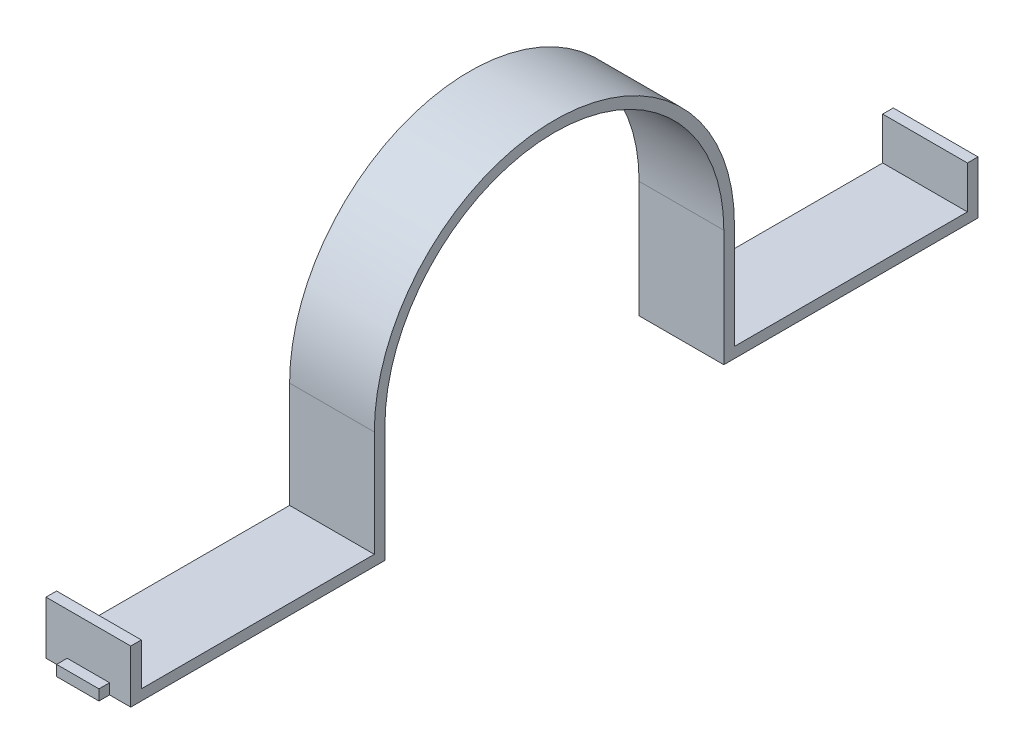
SolidWorks part; units mm, degrees
ref_plane "Front Plane" through (0, 0, 0) normal (0, 0, 1) x (1, 0, 0)
ref_plane "Top Plane" through (0, 0, 0) normal (0, 1, 0) x (1, 0, 0)
ref_plane "Right Plane" through (0, 0, 0) normal (1, 0, 0) x (0, 0, -1)
sketch "Sketch1" plane through (0, 0, 0) normal (1, 0, 0) x (0, 0, -1)
  line L2 (-107.95, 0) -> (-107.95, -69.85)
  line L3 (-107.95, -69.85) -> (-101.6, -69.85)
  line L4 (-101.6, -69.85) -> (-101.6, 0)
  line L6 (101.6, -69.85) -> (107.95, -69.85)
  line L7 (107.95, -69.85) -> (107.95, 0)
  line L8 (101.6, 0) -> (101.6, -69.85)
  arc A0 (-101.6, 0) -> (101.6, 0) centre (0, 0) cw
  arc A2 (-107.95, 0) -> (107.95, 0) centre (0, 0) cw
  point P9 (0, 101.6)
  dimension "D1" = 101.6
  dimension "D2" = 107.95
  dimension "D3" = 101.6
  dimension "D4" = 69.85
extrude "Boss-Extrude1" add sketch "Sketch1" along normal mid plane 50.8
ref_plane "Plane1" through (0, 0, 254) normal (0, 0, 1) x (1, 0, 0)
sketch "Sketch2" plane through (0, 0, 254) normal (0, 0, 1) x (1, 0, 0)
  line L0 (25.4, 0) -> (25.4, 107.95) construction
  line L1 (-25.4, -69.85) -> (25.4, -69.85)
  line L2 (-25.4, -69.85) -> (-25.4, -63.5)
  line L3 (-25.4, -63.5) -> (25.4, -63.5)
  line L4 (25.4, -69.85) -> (25.4, -63.5)
  dimension "D1" = 6.35
extrude "Boss-Extrude2" add sketch "Sketch2" against normal up to body separate body
mirror "Mirror1" about plane through (0, 0, 0) normal (0, 0, 1) of "Boss-Extrude2"
sketch "Sketch3" plane through (0, -63.5, 0) normal (0, 1, 0) x (1, 0, 0)
  line L0 (-27.94, -254) -> (27.94, -254) construction
  line L1 (-12.7, -254) -> (12.7, -254)
  line L2 (-12.7, -254) -> (-12.7, -260.35)
  line L3 (-12.7, -260.35) -> (12.7, -260.35)
  line L4 (12.7, -254) -> (12.7, -260.35)
  line L5 (-25.4, -107.95) -> (-25.4, -254) construction
  dimension "D1" = 25.4
  dimension "D2" = 6.35
  dimension "D3" = 12.7
extrude "Boss-Extrude3" add sketch "Sketch3" against normal up to surface (6.35 mm away) up to face at (0, -69.85, 177.8)
mirror "Mirror2" about plane through (0, 0, 0) normal (0, 0, 1) of "Boss-Extrude3"
sketch "Sketch4" plane through (0, -63.5, 0) normal (0, 1, 0) x (1, 0, 0)
  line L0 (25.4, -107.95) -> (25.4, -254) construction
  line L1 (-25.4, -254) -> (25.4, -254)
  line L2 (-25.4, -254) -> (-25.4, -247.65)
  line L3 (-25.4, -247.65) -> (25.4, -247.65)
  line L4 (25.4, -254) -> (25.4, -247.65)
  dimension "D1" = 6.35
extrude "Boss-Extrude4" add sketch "Sketch4" along normal blind 25.4
mirror "Mirror3" about plane through (0, 0, 0) normal (0, 0, 1) of "Boss-Extrude4"
